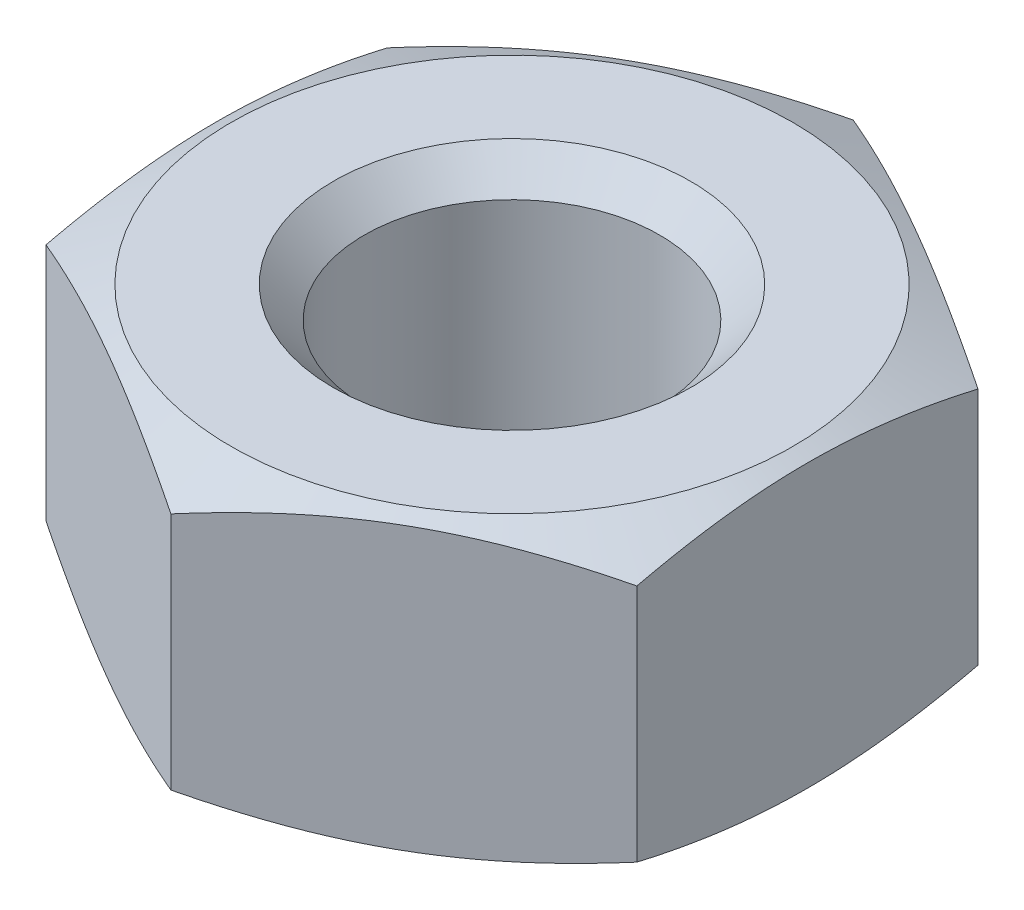
SolidWorks part; units mm, degrees
material "Galvanized Steel"
ref_plane "Front Plane" through (0, 0, 0) normal (0, 0, 1) x (1, 0, 0)
ref_plane "Top Plane" through (0, 0, 0) normal (0, 1, 0) x (1, 0, 0)
ref_plane "Right Plane" through (0, 0, 0) normal (1, 0, 0) x (0, 0, -1)
sketch "Sketch1" plane through (0, 0, 0) normal (0, 1, 0) x (1, 0, 0)
  line L1 (0, 5.7735) -> (-5, 2.8868)
  line L2 (-5, 2.8868) -> (-5, -2.8868)
  line L3 (-5, -2.8868) -> (0, -5.7735)
  line L4 (0, -5.7735) -> (5, -2.8868)
  line L5 (5, -2.8868) -> (5, 2.8868)
  line L6 (5, 2.8868) -> (0, 5.7735)
  circle A0 centre (0, 0) radius 5 construction
  dimension "D1" = 10
extrude "Boss-Extrude1" add sketch "Sketch1" along normal mid plane 5
sketch "Sketch2" plane through (0, 0, 0) normal (0, 0, 1) x (1, 0, 0)
  line L0 (-4.7527, 2.5) -> (-5.825, 2)
  line L1 (-5.825, 2) -> (-5.825, 2.5)
  line L2 (-5.825, 2.5) -> (-4.7527, 2.5)
  line L3 (0, 0) -> (0, 3.4047) construction
  line L4 (-5, 2.5) -> (0, 2.5) construction
  dimension "D1" = 5.825
  dimension "D2" = 25
  dimension "D3" = 0.5
revolve "Cut-Revolve1" cut sketch "Sketch2" angle 360 about L3
mirror "Mirror1" about plane through (0, 0, 0) normal (0, 1, 0) of "Cut-Revolve1"
hole_wizard "M6 Tapped Hole1" positions "Sketch3" profile "Sketch4" tap size "M6" standard "DIN" end condition through all
sketch "Sketch3" plane through (0, 2.5, 0) normal (0, 1, 0) x (1, 0, 0)
  point P0 (0, 0)
sketch "Sketch4" plane through (0, 2.5, 0) normal (1, 0, 0) x (0, 0, 1)
  line L0 (0, 0) -> (0, 5)
  line L1 (0, 5) -> (3.025, 5)
  line L2 (2.5, 4.475) -> (2.5, 0.525)
  line L3 (2.5, 0.525) -> (3.025, 0)
  line L5 (3.025, 0) -> (0, 0)
  line L6 (-2.5, 0.525) -> (-3.025, 0) construction
  line L7 (3.025, 5) -> (2.5, 4.475)
  line L8 (-3.025, 5) -> (-2.5, 4.475) construction
  line L11 (0, -6.35) -> (0, 107.95) construction
  dimension "Thru Tap Drill Dia." = 5
  dimension "Thru Tap Drill Depth" = 5
  dimension "Near C'Sink Dia." = 6.05
  dimension "Near C'Sink Angle" = 90
  dimension "Far C'Sink Dia." = 6.05
  dimension "Far C'Sink Angle" = 90
cosmetic thread "Hole Thread1" parameters "D2"=6
